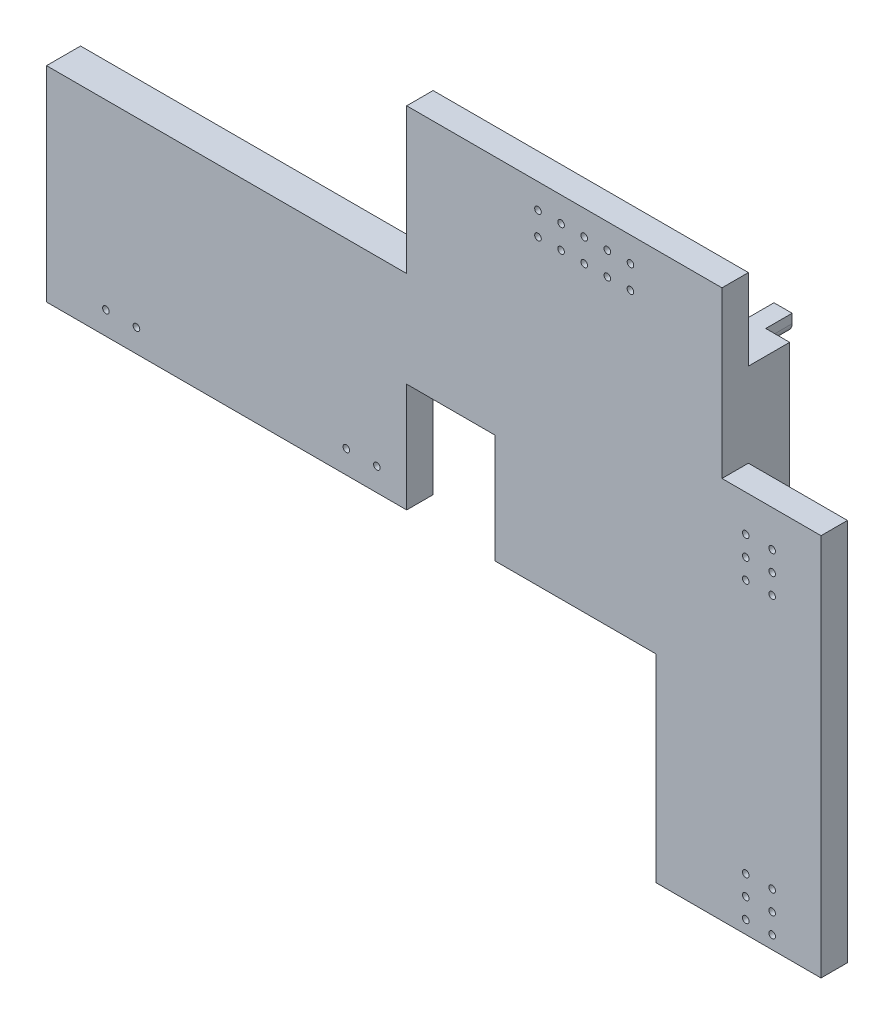
SolidWorks part; units mm, degrees
material "ABS"
ref_plane "前视基准面" through (0, 0, 0) normal (0, 0, 1) x (1, 0, 0)
ref_plane "上视基准面" through (0, 0, 0) normal (0, 1, 0) x (1, 0, 0)
ref_plane "右视基准面" through (0, 0, 0) normal (1, 0, 0) x (0, 0, -1)
other "Configuration Table"
sketch "草图2" plane through (0, 0, 0) normal (0, 0, 1) x (1, 0, 0)
  line L0 (-27.2634, 8) -> (-27.2634, -8) construction
  line L1 (-27.2634, 45) -> (75, 45)
  line L2 (-27.2634, 45) -> (-27.2634, -38)
  line L3 (-27.2634, -38) -> (75, -38)
  line L4 (75, 45) -> (75, -38)
  line L6 (27.2634, -8) -> (-27.2634, -8) construction
  line L7 (28, 8) -> (28, -7) construction
  dimension "D1" = 45
  dimension "D2" = 30
  dimension "D3" = 47
extrude "凸台-拉伸1" add sketch "草图2" along normal blind 4
sketch "草图4" plane through (0, 0, 0) normal (0, 0, -1) x (-1, 0, 0)
  line L0 (27.2634, 45) -> (27.2634, -38) construction
  line L1 (-27.2634, 23) -> (27.2634, 23)
  line L2 (-27.2634, 23) -> (-27.2634, 17)
  line L3 (-27.2634, 17) -> (27.2634, 17)
  line L4 (27.2634, 23) -> (27.2634, 17)
  line L6 (-39.5805, 20) -> (-39.2395, 20) construction
  line L7 (-27.2634, -8) -> (-27.2634, 8) construction
  dimension "D2" = 3
  dimension "D3" = 3
extrude "凸台-拉伸2" add sketch "草图4" along normal up to surface (1.15 mm away)
sketch "草图5" plane through (0, 0, 0) normal (0, 0, -1) x (-1, 0, 0)
  line L0 (-27.2634, 23) -> (-27.2634, 17) construction
  line L1 (-75, 32.73) -> (-27.2634, 32.73)
  line L2 (-75, 32.73) -> (-75, 7.27)
  line L3 (-75, 7.27) -> (-27.2634, 7.27)
  line L4 (-27.2634, 32.73) -> (-27.2634, 7.27)
  line L5 (-75, -38) -> (-75, 45) construction
  line L8 (17.65, 29.73) -> (-100.05, 29.73) construction
  line L9 (17.65, 10.27) -> (-100.05, 10.27) construction
  dimension "D1" = 3
  dimension "D2" = 3
extrude "凸台-拉伸3" add sketch "草图5" along normal up to surface (6.25 mm away)
sketch "草图6" plane through (0, 0, -6.25) normal (0, 0, -1) x (-1, 0, 0)
  line L1 (-40.15, 7.5) -> (-40.15, -6.5) construction
  line L2 (-75, 7.27) -> (-27.2634, 7.27) construction
  line L3 (-71.375, 10.02) -> (-68.625, 10.02)
  line L4 (-27.2634, 32.73) -> (-75, 32.73)
  line L5 (-75, 32.73) -> (-75, 7.27)
  line L6 (-75, 7.27) -> (-27.2634, 7.27)
  line L7 (-27.2634, 7.27) -> (-27.2634, 32.73)
  line L8 (-27.2634, 32.73) -> (-75, 32.73)
  line L9 (-75, 32.73) -> (-75, 7.27)
  line L10 (-75, 7.27) -> (-27.2634, 7.27)
  line L11 (-27.2634, 7.27) -> (-27.2634, 32.73)
  line L12 (-71.375, 10.02) -> (-71.375, 7.27)
  line L13 (-71.375, 7.27) -> (-68.625, 7.27)
  line L14 (-68.625, 10.02) -> (-68.625, 7.27)
  line L15 (-71.375, 10.02) -> (-68.625, 7.27) construction
  line L16 (-71.375, 7.27) -> (-68.625, 10.02) construction
  line L17 (-27.2634, 32.73) -> (-75, 32.73) construction
  line L18 (-44.525, 10.02) -> (-41.775, 10.02)
  line L19 (-44.525, 10.02) -> (-44.525, 7.27)
  line L20 (-44.525, 7.27) -> (-41.775, 7.27)
  line L21 (-41.775, 10.02) -> (-41.775, 7.27)
  line L22 (-44.525, 10.02) -> (-41.775, 7.27) construction
  line L23 (-44.525, 7.27) -> (-41.775, 10.02) construction
  line L24 (-71.375, 29.98) -> (-68.625, 29.98)
  line L25 (-71.375, 29.98) -> (-71.375, 32.73)
  line L26 (-71.375, 32.73) -> (-68.625, 32.73)
  line L27 (-68.625, 29.98) -> (-68.625, 32.73)
  line L28 (-71.375, 29.98) -> (-68.625, 32.73) construction
  line L29 (-71.375, 32.73) -> (-68.625, 29.98) construction
  line L30 (-33.6384, 32.73) -> (-30.8884, 32.73)
  line L31 (-33.6384, 32.73) -> (-33.6384, 29.98)
  line L32 (-33.6384, 29.98) -> (-30.8884, 29.98)
  line L33 (-30.8884, 32.73) -> (-30.8884, 29.98)
  line L34 (-33.6384, 32.73) -> (-30.8884, 29.98) construction
  line L35 (-33.6384, 29.98) -> (-30.8884, 32.73) construction
  circle A0 centre (-70, 31.355) radius 1.375
  circle A1 centre (-32.2634, 31.355) radius 1.375
  circle A2 centre (-70, 8.645) radius 1.375
  circle A3 centre (-43.15, 8.645) radius 1.375
  dimension "D2" = 2.75
  dimension "D3" = 2.75
  dimension "D4" = 5
  dimension "D5" = 5
  dimension "D6" = 3
  dimension "D1" = 0
extrude "凸台-拉伸4" add sketch "草图6" along normal blind 4 contours A0 | A2 | A3 | A1 | A0 L26 L25 | A0 L27 L8 | A1 L33 L8 | A1 L30 L31 | A2 L12 L10 | A2 L13 L14 | A3 L20 L21 | A3 L19 L10
sketch "草图7" plane through (0, 0, -6.25) normal (0, 0, -1) x (-1, 0, 0)
  line L0 (-41.775, 7.27) -> (-27.2634, 7.27) construction
  line L1 (-40.65, 7.27) -> (-27.2634, 7.27)
  line L2 (-40.65, 7.27) -> (-40.65, 8.5)
  line L3 (-40.65, 8.5) -> (-27.2634, 8.5)
  line L4 (-27.2634, 7.27) -> (-27.2634, 8.5)
  line L5 (-27.2634, 7.27) -> (-27.2634, 32.73) construction
  line L6 (-40.15, 7.5) -> (-40.15, -6.5) construction
  line L7 (27.1971, 8) -> (-27.2634, 8) construction
  dimension "D1" = 0.5
  dimension "D2" = 0.5
extrude "切除-拉伸1" cut sketch "草图7" against normal through all
sketch "草图8" plane through (0, 0, 0) normal (0, 0, -1) x (-1, 0, 0)
  line L1 (-40.65, -8) -> (-27.2634, -8)
  line L2 (-40.65, -8) -> (-40.65, 8.5)
  line L3 (-40.65, 8.5) -> (-27.2634, 8.5)
  line L4 (-27.2634, -8) -> (-27.2634, 8.5)
  line L5 (-27.2634, 8.5) -> (-27.2634, 32.73) construction
  line L6 (-40.65, 8.5) -> (-40.65, 7.27) construction
  line L7 (-27.2634, 8.5) -> (-40.65, 8.5) construction
  line L8 (-27.2634, -8) -> (27.2634, -8) construction
extrude "切除-拉伸3" cut sketch "草图8" against normal through all
sketch "草图9" plane through (0, 0, 0) normal (0, 0, 1) x (1, 0, 0)
  line L1 (75, 45) -> (90, 45)
  line L2 (75, 45) -> (75, -38)
  line L3 (75, -38) -> (90, -38)
  line L4 (90, 45) -> (90, -38)
  line L5 (75, 45) -> (-27.2634, 45) construction
  line L10 (75, -38) -> (75, 45) construction
  dimension "D1" = 15
extrude "凸台-拉伸5" add sketch "草图9" along normal up to surface (4 mm away) up to face at (33.9567, 0.25, 4)
sketch "草图10" plane through (0, 0, 0) normal (0, 0, -1) x (-1, 0, 0)
  circle A0 centre (-78.6, 8.47) radius 0.5
  circle A1 centre (-82.6, 8.47) radius 0.5
  dimension "D1" = 1
  dimension "D2" = 1
extrude "切除-拉伸4" cut sketch "草图10" against normal through all
pattern_linear "阵列(线性)1" count 3 spacing 3 along (0, 1, 0) of "切除-拉伸4"
pattern_linear "阵列(线性)2" count 2 spacing 44.5 along (0, -1, 0) of "阵列(线性)1", "切除-拉伸4"
sketch "草图12" plane through (0, 0, 0) normal (0, 0, -1) x (-1, 0, 0)
  circle A0 centre (-61.1435, 41.2411) radius 0.5
  circle A1 centre (-61.1435, 37.7411) radius 0.5
  dimension "D1" = 1
  dimension "D2" = 1
extrude "切除-拉伸5" cut sketch "草图12" against normal through all
pattern_linear "阵列(线性)3" count 5 spacing 3.5 along (-1, 0, 0) of "切除-拉伸5"
sketch "草图13" plane through (0, 0, 0) normal (0, 0, -1) x (-1, 0, 0)
  circle A0 centre (-22.75, -4.52) radius 0.5
  circle A1 centre (-18.125, -4.52) radius 0.5
  circle A2 centre (13.65, -4.52) radius 0.5
  circle A3 centre (18.27, -4.52) radius 0.5
  dimension "D1" = 1
  dimension "D2" = 1
  dimension "D3" = 1
  dimension "D4" = 1
extrude "切除-拉伸6" cut sketch "草图13" against normal through all
sketch "草图14" plane through (0, 0, 0) normal (0, 0, -1) x (-1, 0, 0)
  line L0 (-40.65, -8) -> (-27.2634, -8) construction
  line L1 (27.2634, -38) -> (-65, -38)
  line L2 (27.2634, -38) -> (27.2634, -8)
  line L3 (27.2634, -8) -> (-65, -8)
  line L4 (-65, -38) -> (-65, -8)
  line L5 (-90, 45) -> (-90, -38) construction
  line L6 (-75, 32.73) -> (-75, 7.27) construction
  line L7 (-90, 45) -> (-75, 45)
  line L8 (-90, 45) -> (-90, 20)
  line L9 (-90, 20) -> (-75, 20)
  line L10 (-75, 45) -> (-75, 20)
  line L12 (27.2634, 45) -> (-27.2634, 45)
  line L13 (27.2634, 45) -> (27.2634, 23)
  line L14 (27.2634, 23) -> (-27.2634, 23)
  line L15 (-27.2634, 45) -> (-27.2634, 23)
  point P7 (-65, -23)
  dimension "D1" = 25
  dimension "D2" = 25
extrude "切除-拉伸7" cut sketch "草图14" against normal through all
